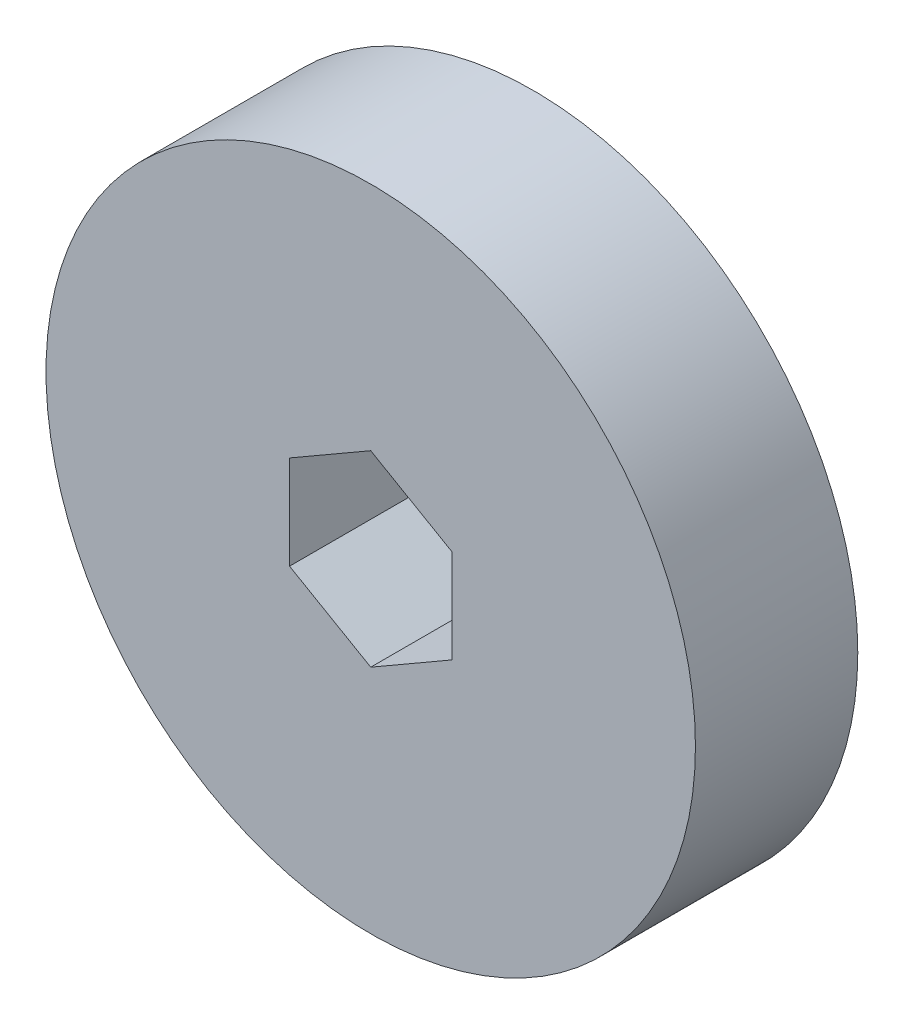
SolidWorks part; units mm, degrees
material "ABS"
ref_plane "Front Plane" through (0, 0, 0) normal (0, 0, 1) x (1, 0, 0)
ref_plane "Top Plane" through (0, 0, 0) normal (0, 1, 0) x (1, 0, 0)
ref_plane "Right Plane" through (0, 0, 0) normal (1, 0, 0) x (0, 0, -1)
sketch "Sketch1" plane through (0, 0, 0) normal (0, 0, 1) x (1, 0, 0)
  line L1 (0, -1.8331) -> (1.5875, -0.9165)
  line L2 (1.5875, -0.9165) -> (1.5875, 0.9165)
  line L3 (1.5875, 0.9165) -> (0, 1.8331)
  line L4 (0, 1.8331) -> (-1.5875, 0.9165)
  line L5 (-1.5875, 0.9165) -> (-1.5875, -0.9165)
  line L6 (-1.5875, -0.9165) -> (0, -1.8331)
  circle A0 centre (0, 0) radius 6.35
  circle A1 centre (0, 0) radius 1.5875 construction
  dimension "D1" = 12.7
  dimension "D2" = 3.175
extrude "Boss-Extrude1" add sketch "Sketch1" along normal blind 3.175
